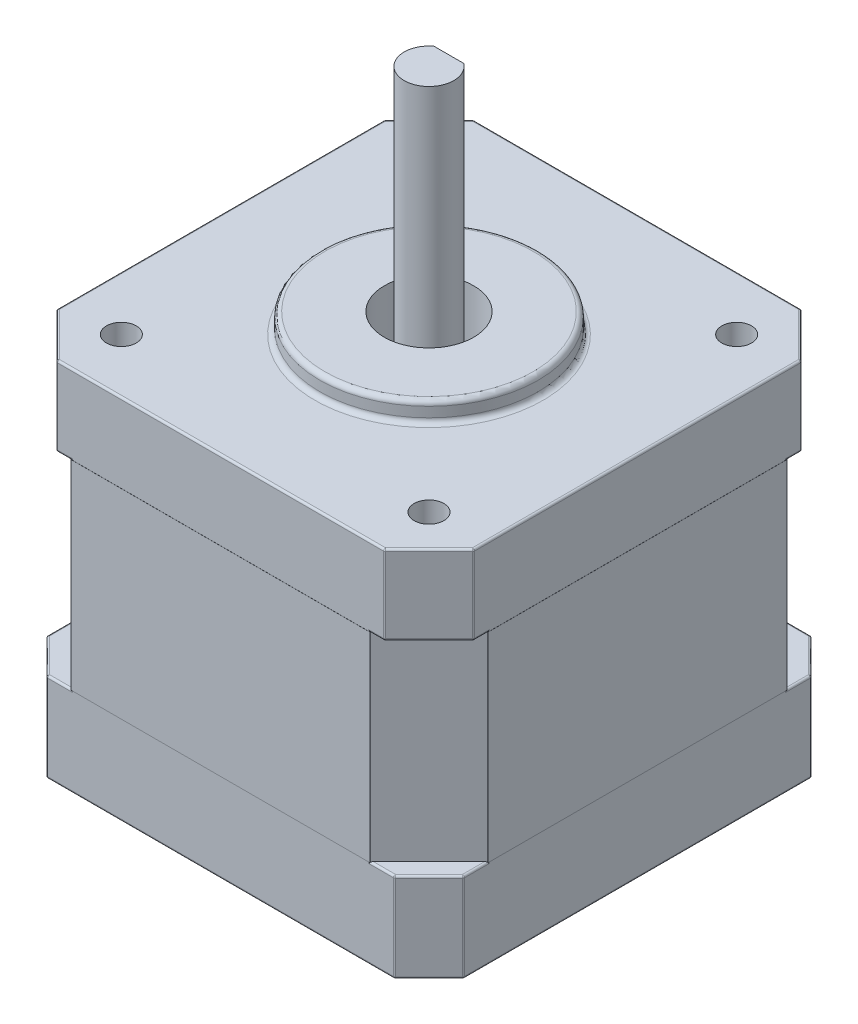
SolidWorks part; units mm, degrees
ref_plane "Ön Düzlem" through (0, 0, 0) normal (0, 0, 1) x (1, 0, 0)
ref_plane "Üst Düzlem" through (0, 0, 0) normal (0, 1, 0) x (1, 0, 0)
ref_plane "Sağ Düzlem" through (0, 0, 0) normal (1, 0, 0) x (0, 0, -1)
sketch "Çizim1" plane through (0, 0, 0) normal (0, 1, 0) x (1, 0, 0)
  line L0 (-21, 17.5) -> (-17.5, 21)
  line L1 (-17.5, 21) -> (-8, 21)
  line L2 (-21, 17.5) -> (-21, -17.5)
  line L3 (-17.5, -21) -> (17.5, -21)
  line L4 (21, 17.5) -> (21, -17.5)
  line L5 (-21, 21) -> (21, -21) construction
  line L6 (-21, -21) -> (21, 21) construction
  line L7 (17.5, 21) -> (21, 17.5)
  line L8 (17.5, -21) -> (21, -17.5)
  line L9 (-21, -17.5) -> (-17.5, -21)
  line L11 (0, 0) -> (20.5054, -0.6314) construction
  line L12 (-8, 25) -> (8, 25)
  line L13 (-8, 25) -> (-8, 21)
  line L15 (8, 25) -> (8, 21)
  line L17 (-15.5, -15.5) -> (15.5, -15.5) construction
  line L18 (8, 21) -> (17.5, 21)
  line L19 (-15.5, -15.5) -> (-15.5, 15.5) construction
  line L20 (-15.5, 15.5) -> (15.5, 15.5) construction
  line L21 (15.5, -15.5) -> (15.5, 15.5) construction
  line L22 (-15.5, -15.5) -> (15.5, 15.5) construction
  line L23 (-15.5, 15.5) -> (15.5, -15.5) construction
  circle A4 centre (0, 0) radius 4.5
  circle A5 centre (15.5, 15.5) radius 1.5
  circle A6 centre (15.5, -15.5) radius 1.5
  circle A7 centre (-15.5, -15.5) radius 1.5
  circle A8 centre (-15.5, 15.5) radius 1.5
  point P0 (0, 0)
  point P26 (0, 21)
  dimension "D10" = 9
  dimension "D11" = 16
  dimension "D4" = 3
  dimension "D1" = 42
  dimension "D2" = 42
  dimension "D3" = 31
extrude "Yükseklik-Ekstrüzyon1" add sketch "Çizim1" along normal blind 9
sketch "Çizim2" plane through (0, 9, 0) normal (0, 1, 0) x (1, 0, 0)
  line L1 (8, 25) -> (-8, 25)
  line L2 (8, 25) -> (8, 21)
  line L3 (8, 21) -> (-8, 21)
  line L4 (-8, 25) -> (-8, 21)
extrude "Kes-Ekstrüzyon1" cut sketch "Çizim2" against normal blind 6
sketch "Çizim3" plane through (0, 0, -21) normal (0, 0, -1) x (-1, 0, 0)
  line L0 (-8, 3) -> (-8, 4) construction
  line L1 (-8, 4) -> (8, 4) construction
  line L2 (-17.5, 9) -> (17.5, 9) construction
  line L3 (-8, 4) -> (8, 4)
  line L4 (-8, 4) -> (-8, 9)
  line L5 (-8, 9) -> (8, 9)
  line L6 (8, 4) -> (8, 9)
  dimension "D1" = 1
extrude "Yükseklik-Ekstrüzyon2" add sketch "Çizim3" along normal blind 0.5
sketch "Çizim4" plane through (0, 0, -21.5) normal (0, 0, -1) x (-1, 0, 0)
  line L0 (4, 9) -> (8, 9)
  line L1 (8, 9) -> (-8, 9) construction
  line L2 (8, 9) -> (8, 4)
  line L3 (8, 4) -> (-8, 4)
  line L4 (-8, 4) -> (-8, 9)
  line L5 (-8, 9) -> (-4, 9)
  line L6 (4, 8.5) -> (7.5, 8.5)
  line L7 (7.5, 8.5) -> (7.5, 4.5)
  line L8 (7.5, 4.5) -> (-7.5, 4.5)
  line L9 (-7.5, 4.5) -> (-7.5, 8.5)
  line L10 (-7.5, 8.5) -> (-4, 8.5)
  line L11 (-4, 9) -> (-4, 8.5)
  line L12 (4, 9) -> (4, 8.5)
  dimension "D1" = 4
  dimension "D2" = 4
  dimension "D3" = 0.5
extrude "Yükseklik-Ekstrüzyon3" add sketch "Çizim4" along normal blind 5
sketch "Çizim7" plane through (0, 9, 0) normal (0, 1, 0) x (1, 0, 0)
  line L0 (21, -17.5) -> (21, 17.5) construction
  line L1 (-15, 21) -> (15, 21)
  line L2 (-21, 15) -> (-21, -15)
  line L3 (-15, -21) -> (15, -21)
  line L4 (21, 15) -> (21, -15)
  line L5 (-21, 21) -> (21, -21) construction
  line L6 (-21, -21) -> (21, 21) construction
  line L7 (-17.5, -21) -> (17.5, -21) construction
  line L8 (-21, 15) -> (-15, 21)
  line L9 (15, 21) -> (21, 15)
  line L10 (15, -21) -> (21, -15)
  line L11 (-21, -15) -> (-15, -21)
  circle A0 centre (0, 0) radius 4.5
  point P0 (0, 0)
extrude "Yükseklik-Ekstrüzyon4" add sketch "Çizim7" along normal blind 20
sketch "Çizim8" plane through (0, 29, 0) normal (0, 1, 0) x (1, 0, 0)
  line L0 (-15, -21) -> (15, -21) construction
  line L1 (-16.5, 21) -> (16.5, 21)
  line L2 (-21, 16.5) -> (-21, -16.5)
  line L3 (-16.5, -21) -> (16.5, -21)
  line L4 (21, 16.5) -> (21, -16.5)
  line L5 (-21, 21) -> (21, -21) construction
  line L6 (-21, -21) -> (21, 21) construction
  line L7 (21, -15) -> (21, 15) construction
  line L8 (-21, 16.5) -> (-16.5, 21)
  line L9 (16.5, 21) -> (21, 16.5)
  line L10 (16.5, -21) -> (21, -16.5)
  line L11 (-21, -16.5) -> (-16.5, -21)
  circle A0 centre (0, 0) radius 4.5
  point P0 (0, 0)
extrude "Yükseklik-Ekstrüzyon5" add sketch "Çizim8" along normal blind 8
sketch "Çizim10" plane through (0, 37, 0) normal (0, 1, 0) x (1, 0, 0)
  circle A0 centre (0, 0) radius 4.5
  circle A1 centre (0, 0) radius 11
  dimension "D1" = 22
extrude "Yükseklik-Ekstrüzyon6" add sketch "Çizim10" along normal blind 2
fillet "Radyus1" radius 0.5 2 edges at (0, 37, -11) (0, 39, 11)
fillet "Radyus2" radius 0.2 76 edges at (-21, 9, -16.25) (-8, 0, -23) (0, 0, -25) (8, 0, -23) (-16.25, 9, -21) (-21, 9, 16.25) (16.25, 9, 21) (21, 9, -16.25) (12.75, 0, -21) (19.25, 0, -19.25) (-15, 19, -21) (-21, 19, -15) (-21, 19, 15) (-15, 19, 21) (15, 19, 21) (21, 19, 15) (21, 19, -15) (21, 0, 0) (15, 19, -21) (-19.25, 9, 19.25) (19.25, 0, 19.25) (0, 0, 21) (-19.25, 0, 19.25) (-21, 0, 0) (-19.25, 0, -19.25) (-12.75, 0, -21) (-18.75, 37, -18.75) (-21, 37, 0) (-18.75, 37, 18.75) (0, 37, 21) (18.75, 37, 18.75) (21, 37, 0) (18.75, 37, -18.75) (0, 37, -21) (-18.75, 29, -18.75) (-16.5, 33, -21) (-21, 29, -15.75) (-21, 29, 15.75) (-21, 33, -16.5) (-18.75, 29, 18.75) (-21, 33, 16.5) (-15.75, 29, 21) (15.75, 29, 21) (-16.5, 33, 21) (18.75, 29, 18.75) (-16.25, 9, 21) (16.5, 33, 21) (21, 29, 15.75) (21, 29, -15.75) (21, 33, 16.5) (18.75, 29, -18.75) (21, 33, -16.5) (15.75, 29, -21) (-15.75, 29, -21) (16.5, 33, -21) (19.25, 9, 19.25) (17.5, 4.5, -21) (21, 4.5, -17.5) (21, 4.5, 17.5) (17.5, 4.5, 21) (-17.5, 4.5, 21) (-21, 4.5, 17.5) (-21, 4.5, -17.5) (-17.5, 4.5, -21) (21, 9, 16.25) (19.25, 9, -19.25) (16.25, 9, -21) (-8, 1.5, -21) (-8, 1.5, -25) (8, 1.5, -25) (8, 1.5, -21) (8, 3, -23) (0, 3, -21) (-8, 3, -23) (0, 3, -25) (-19.25, 9, -19.25)
ref_plane "Düzlem1" through (0, 16.5, 0) normal (0, -1, 0) x (-1, 0, 0)
sketch "Çizim11" plane through (0, 16.5, 0) normal (0, -1, 0) x (-1, 0, 0)
  circle A0 centre (0, 0) radius 4.5
  circle A1 centre (0, 0) radius 2.5
  dimension "D1" = 5
extrude "Yükseklik-Ekstrüzyon7" add sketch "Çizim11" along normal blind 11.5 and the other way blind 11.5
sketch "Çizim12" plane through (0, 5, 0) normal (0, -1, 0) x (1, 0, 0)
  circle A0 centre (0, 0) radius 2.5
extrude "Yükseklik-Ekstrüzyon8" add sketch "Çizim12" against normal blind 55.4
sketch "Çizim14" plane through (0, 0, -21.5) normal (0, 0, -1) x (-1, 0, 0)
  line L0 (-7.5, 7) -> (7.5, 7) construction
  line L1 (-7.5, 4.5) -> (-7.5, 8.5) construction
  line L2 (7.5, 8.5) -> (7.5, 4.5) construction
  line L3 (-8, 9) -> (8, 9) construction
  line L4 (0, 7) -> (0, 9) construction
  circle A0 centre (-1.25, 7) radius 0.25
  circle A1 centre (-3.75, 7) radius 0.25
  circle A2 centre (-6.25, 7) radius 0.25
  circle A3 centre (1.25, 7) radius 0.25
  circle A4 centre (3.75, 7) radius 0.25
  circle A5 centre (6.25, 7) radius 0.25
  point P12 (0, 8)
  dimension "D2" = 0.5
  dimension "D3" = 1.25
  dimension "D1" = 2
  dimension "D4" = 3
extrude "Yükseklik-Ekstrüzyon9" add sketch "Çizim14" along normal blind 3
sketch "Çizim15" plane through (0, 0, -21) normal (0, 0, -1) x (-1, 0, 0)
  line L0 (0, 4) -> (0, 3.2) construction
  line L1 (-8, 4) -> (8, 4) construction
  line L2 (-7.8, 3.2) -> (7.8, 3.2) construction
  line L3 (8, 4) -> (8, 9) construction
  line L4 (-8, 3.85) -> (8, 3.85)
  line L5 (-8, 3.85) -> (-8, 3.35)
  line L6 (-8, 3.35) -> (8, 3.35)
  line L7 (8, 3.85) -> (8, 3.35)
  line L8 (-8, 3.85) -> (8, 3.35) construction
  line L9 (-8, 3.35) -> (8, 3.85) construction
  point P6 (0, 3.6)
  dimension "D1" = 0.5
extrude "Yükseklik-Ekstrüzyon11" add sketch "Çizim15" along normal through all
sketch "Çizim17" plane through (21, 0, 0) normal (1, 0, 0) x (0, 0, -1)
  line L1 (-15.0586, 29.0586) -> (15.0586, 29.0586)
  line L2 (-15.0586, 29.0586) -> (-15.0586, 8.9414)
  line L3 (-15.0586, 8.9414) -> (15.0586, 8.9414)
  line L4 (15.0586, 29.0586) -> (15.0586, 8.9414)
extrude "Yükseklik-Ekstrüzyon13" add sketch "Çizim17" along normal blind 0.01
sketch "Çizim18" plane through (0, 0, -21) normal (0, 0, -1) x (-1, 0, 0)
  line L1 (-15.0586, 29.0586) -> (15.0586, 29.0586)
  line L2 (-15.0586, 29.0586) -> (-15.0586, 8.9414)
  line L3 (-15.0586, 8.9414) -> (15.0586, 8.9414)
  line L4 (15.0586, 29.0586) -> (15.0586, 8.9414)
extrude "Yükseklik-Ekstrüzyon14" add sketch "Çizim18" along normal blind 0.01
sketch "Çizim19" plane through (-21, 0, 0) normal (-1, 0, 0) x (0, 0, 1)
  line L1 (-15.0586, 29.0586) -> (15.0586, 29.0586)
  line L2 (-15.0586, 29.0586) -> (-15.0586, 8.9414)
  line L3 (-15.0586, 8.9414) -> (15.0586, 8.9414)
  line L4 (15.0586, 29.0586) -> (15.0586, 8.9414)
extrude "Yükseklik-Ekstrüzyon15" add sketch "Çizim19" along normal blind 0.01
sketch "Çizim20" plane through (0, 0, 21) normal (0, 0, 1) x (1, 0, 0)
  line L1 (-15.0586, 29.0586) -> (15.0586, 29.0586)
  line L2 (-15.0586, 29.0586) -> (-15.0586, 8.9414)
  line L3 (-15.0586, 8.9414) -> (15.0586, 8.9414)
  line L4 (15.0586, 29.0586) -> (15.0586, 8.9414)
extrude "Yükseklik-Ekstrüzyon16" add sketch "Çizim20" along normal blind 0.01
sketch "Sketch2" plane through (0, 37, 0) normal (0, 1, 0) x (1, 0, 0)
  line L1 (-15.5, 15.5) -> (15.5, 15.5) construction
  line L2 (-15.5, 15.5) -> (-15.5, -15.5) construction
  line L3 (-15.5, -15.5) -> (15.5, -15.5) construction
  line L4 (15.5, 15.5) -> (15.5, -15.5) construction
  line L5 (-15.5, 15.5) -> (15.5, -15.5) construction
  line L6 (-15.5, -15.5) -> (15.5, 15.5) construction
  circle A0 centre (15.5, 15.5) radius 1.5
  circle A1 centre (15.5, -15.5) radius 1.5
  circle A2 centre (-15.5, -15.5) radius 1.5
  circle A3 centre (-15.5, 15.5) radius 1.5
  point P0 (0, 0)
  dimension "D2" = 3
  dimension "D1" = 31
extrude "Cut-Extrude1" cut sketch "Sketch2" against normal blind 3
sketch "Sketch3" plane through (0, 60.4, 0) normal (0, 1, 0) x (1, 0, 0)
  line L0 (0, -2.5) -> (7.0385, -2.5) construction
  line L1 (14.2114, 11.816) -> (-3.7263, 11.816)
  line L2 (14.2114, 11.816) -> (14.2114, 2)
  line L3 (14.2114, 2) -> (-3.7263, 2)
  line L4 (-3.7263, 11.816) -> (-3.7263, 2)
  line L5 (14.2114, 11.816) -> (-3.7263, 2) construction
  line L6 (14.2114, 2) -> (-3.7263, 11.816) construction
  circle A0 centre (0, 0) radius 2.5 construction
  circle A1 centre (0, 0) radius 2.5 construction
  point P0 (5.2426, 6.908)
  dimension "D1" = 4.5
extrude "Cut-Extrude2" cut sketch "Sketch3" against normal blind 17.8
